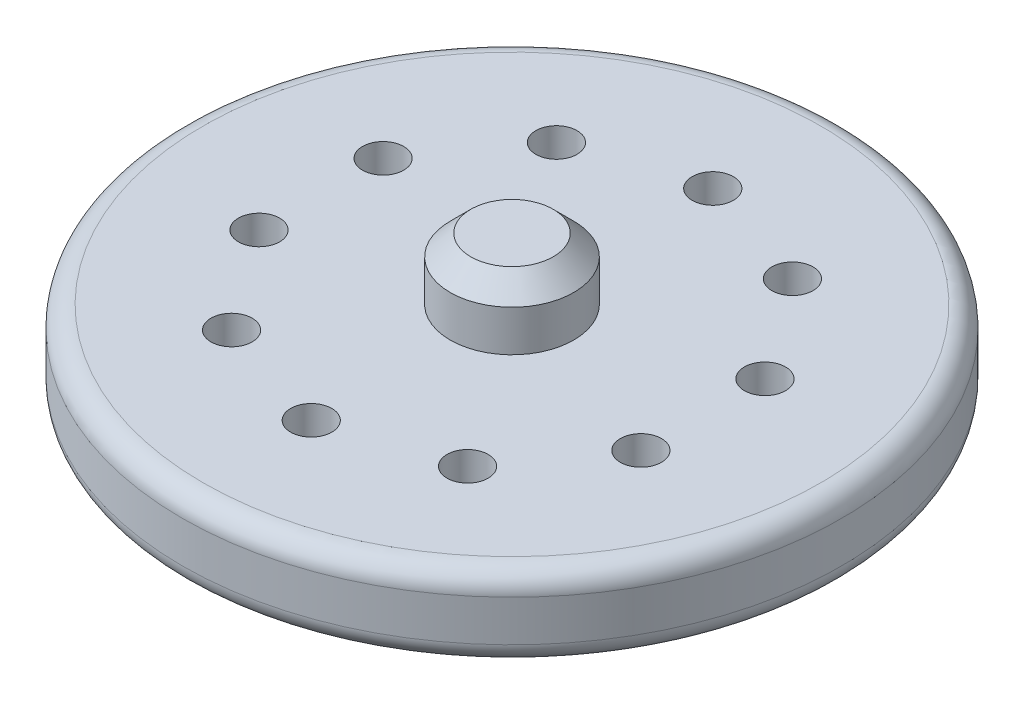
SolidWorks part; units mm, degrees
ref_plane "Front Plane" through (0, 0, 0) normal (0, 0, 1) x (1, 0, 0)
ref_plane "Top Plane" through (0, 0, 0) normal (0, 1, 0) x (1, 0, 0)
ref_plane "Right Plane" through (0, 0, 0) normal (1, 0, 0) x (0, 0, -1)
sketch "Sketch1" plane through (0, 0, 0) normal (0, 1, 0) x (1, 0, 0)
  circle A0 centre (-29.7155, 28.347) radius 80
  dimension "D1" = 160
extrude "Boss-Extrude1" add sketch "Sketch1" along normal blind 20
sketch "Sketch3" plane through (0, 20, 0) normal (0, 1, 0) x (1, 0, 0)
  circle A0 centre (-29.7155, 28.347) radius 15
extrude "Boss-Extrude2" add sketch "Sketch3" along normal blind 15
chamfer "Chamfer1" distance 5 angle 45 1 edges at (-29.7155, 35, -13.347)
fillet "Fillet2" radius 5 1 edges at (-29.7155, 20, 51.653)
fillet "Fillet3" radius 5 1 edges at (-29.7155, 0, 51.653)
sketch "Sketch4" plane through (0, 20, 0) normal (0, 1, 0) x (1, 0, 0)
  circle A0 centre (-29.7155, 77.0813) radius 5
  circle A1 centre (-1.0703, 67.7739) radius 5
  circle A2 centre (16.6335, 43.4067) radius 5
  circle A3 centre (16.6335, 13.2873) radius 5
  circle A4 centre (-1.0703, -11.0798) radius 5
  circle A5 centre (-29.7155, -20.3872) radius 5
  circle A6 centre (-58.3608, -11.0798) radius 5
  circle A7 centre (-76.0645, 13.2873) radius 5
  circle A8 centre (-76.0645, 43.4067) radius 5
  circle A9 centre (-58.3608, 67.7739) radius 5
  point P23 (-29.7155, 28.347)
  dimension "D1" = 10
  dimension "D2" = 10
extrude "Cut-Extrude2" cut sketch "Sketch4" against normal blind 20
